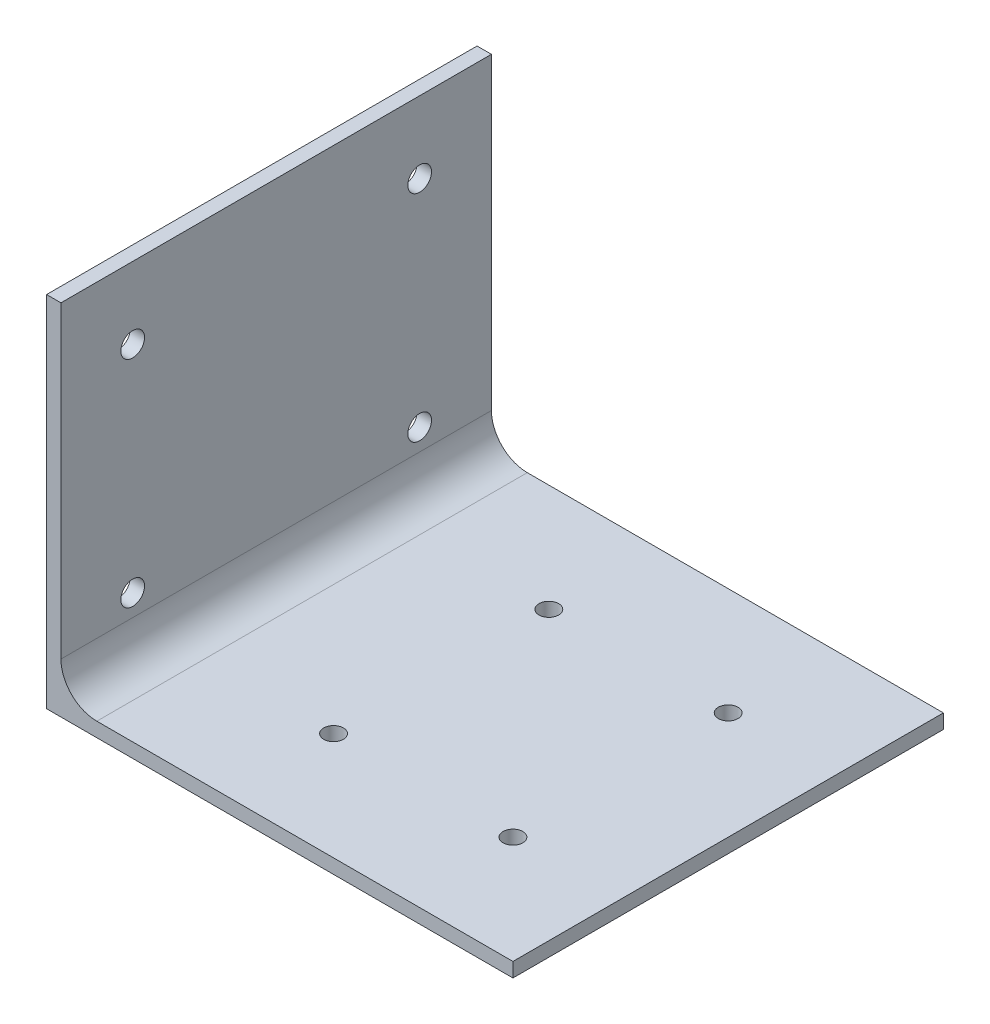
SolidWorks part; units mm, degrees
material "6061-T6 (SS)"
ref_plane "Front Plane" through (0, 0, 0) normal (0, 0, 1) x (1, 0, 0)
ref_plane "Top Plane" through (0, 0, 0) normal (0, 1, 0) x (1, 0, 0)
ref_plane "Right Plane" through (0, 0, 0) normal (1, 0, 0) x (0, 0, -1)
sketch "Sketch2" plane through (0, 0, 0) normal (0, 0, 1) x (1, 0, 0)
  line L0 (0, 0) -> (0, 100)
  line L1 (0, 100) -> (4, 100)
  line L2 (4, 100) -> (4, 4)
  line L3 (4, 4) -> (130, 4)
  line L4 (130, 4) -> (130, 0)
  line L5 (130, 0) -> (0, 0)
  dimension "D1" = 100
  dimension "D2" = 4
  dimension "D3" = 4
  dimension "D4" = 130
extrude "Boss-Extrude1" add sketch "Sketch2" along normal blind 120
sketch "Sketch4" plane through (4, 0, 0) normal (1, 0, 0) x (0, 0, -1)
  line L0 (0, 4) -> (0, 100) construction
  line L1 (-120, 100) -> (0, 100) construction
  circle A0 centre (-100, 80) radius 3.3
  circle A1 centre (-20, 80) radius 3.3
  circle A2 centre (-20, 20) radius 3.3
  circle A3 centre (-100, 20) radius 3.3
  point P8 (0, 0)
  point P9 (0, 0)
  point P10 (0, 0)
  dimension "D1" = 6.6
  dimension "D2" = 60
  dimension "D3" = 80
  dimension "D4" = 20
  dimension "D5" = 20
extrude "Cut-Extrude1" cut sketch "Sketch4" against normal through all
sketch "Sketch5" plane through (0, 4, 0) normal (0, 1, 0) x (1, 0, 0)
  line L0 (0, -120) -> (0, 0) construction
  line L1 (130, -120) -> (4, -120) construction
  circle A0 centre (100, -30) radius 2.75
  circle A1 centre (50, -30) radius 2.75
  circle A2 centre (50, -90) radius 2.75
  circle A3 centre (100, -90) radius 2.75
  point P8 (0, 0)
  point P9 (0, 0)
  point P10 (0, 0)
  dimension "D1" = 5.5
  dimension "D2" = 50
  dimension "D3" = 60
  dimension "D4" = 50
  dimension "D5" = 30
extrude "Cut-Extrude2" cut sketch "Sketch5" against normal through all
fillet "Fillet1" radius 10 1 edges at (4, 4, 60)
